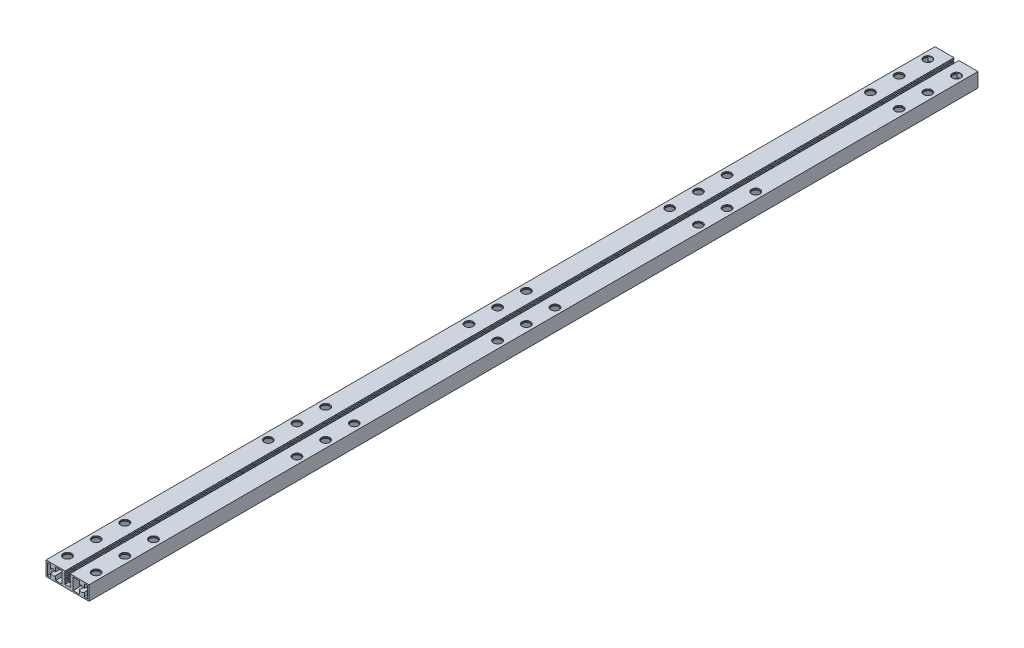
SolidWorks part; units mm, degrees
material "Alliage 6061"
ref_plane "Face" through (0, 0, 0) normal (0, 0, 1) x (1, 0, 0)
ref_plane "Dessus" through (0, 0, 0) normal (0, 1, 0) x (1, 0, 0)
ref_plane "Droite" through (0, 0, 0) normal (1, 0, 0) x (0, 0, -1)
sketch "Esquisse1" plane through (0, 0, 0) normal (0, 0, 1) x (1, 0, 0)
  line L0 (0, 4) -> (0, -4) construction
  line L1 (-12, 4) -> (-1.35, 4)
  line L2 (-12, 4) -> (-12, -4)
  line L3 (-12, -4) -> (12, -4)
  line L4 (12, 4) -> (12, -4)
  line L5 (-12, 0) -> (12, 0) construction
  line L6 (-1.35, 4) -> (-1.35, -2.5)
  line L7 (-1.35, -2.5) -> (1.35, -2.5)
  line L8 (1.35, -2.5) -> (1.35, 4)
  line L9 (1.35, 4) -> (12, 4)
  dimension "D1" = 24
  dimension "D2" = 8
  dimension "D3" = 2.7
  dimension "D4" = 1.5
extrude "Boss.-Extru.1" add sketch "Esquisse1" along normal mid plane 496
sketch "Esquisse2" plane through (0, 0, 248) normal (0, 0, 1) x (1, 0, 0)
  line L0 (-1.35, -2.0613) -> (-2.35, -2.0613) construction
  line L1 (-1.35, -2.5) -> (-1.35, 4) construction
  line L2 (-1.35, -1.7726) -> (-1.35, -2.35)
  line L3 (-1.35, -2.35) -> (-1.85, -2.0613)
  line L4 (-1.85, -2.0613) -> (-1.35, -1.7726)
  dimension "D1" = 0.5
  dimension "D2" = 60
  dimension "D3" = 0.15
extrude "Enlèv. mat.-Extru.1" cut sketch "Esquisse2" against normal through all
pattern_linear "Répétition linéaire1" count 8 spacing 0.8 along (0, 1, 0) of "Enlèv. mat.-Extru.1"
mirror "Symétrie1" about plane through (0, 0, 0) normal (1, 0, 0) of "Répétition linéaire1", "Enlèv. mat.-Extru.1"
sketch "Esquisse3" plane through (0, 0, 248) normal (0, 0, 1) x (1, 0, 0)
  line L0 (0, -4) -> (0, 4.7042) construction
  line L1 (-12, -4) -> (12, -4) construction
  line L5 (-3.1, 3.25) -> (-3.1, -3.25)
  line L6 (-1.35, -2.5) -> (-1.35, -2.35) construction
  line L7 (3.1, 3.25) -> (11.25, 3.25)
  line L8 (-11.25, -3.25) -> (12, -3.25)
  line L11 (-11.25, 3.25) -> (-11.25, -3.25)
  line L12 (-1.35, 3.25) -> (-11.25, 3.25)
  line L13 (-11.25, -3.25) -> (-3.1, -3.25)
  line L14 (-11.25, 3.25) -> (-11.25, -3.25)
  line L15 (-3.1, 3.25) -> (-11.25, 3.25)
  line L16 (11.25, 3.25) -> (11.25, -3.25)
  line L17 (11.25, -3.25) -> (3.1, -3.25)
  line L18 (3.1, 3.25) -> (3.1, -3.25)
  dimension "D1" = 0.75
  dimension "D2" = 1.75
extrude "Enlèv. mat.-Extru.2" cut sketch "Esquisse3" against normal through all
hole_wizard "Dégagement M41" positions "Esquisse5" profile "Esquisse4" hole size "M4" standard "Iso" end condition through all
sketch "Esquisse5" plane through (0, 4, 0) normal (0, 1, 0) x (1, 0, 0)
  line L0 (0, -485.7388) -> (0, -248) construction
  line L1 (-12, -248) -> (12, -248) construction
  line L2 (-1.35, -248) -> (-12, -248) construction
  point P0 (-8, -240)
  point P2 (8, -240)
  dimension "D1" = 8
  dimension "D2" = 16
sketch "Esquisse4" plane through (-8, 4, 240) normal (1, 0, 0) x (0, 0, 1)
  line L0 (0, 0) -> (0, 8)
  line L1 (0, 8) -> (2.35, 8)
  line L2 (2.1, 7.75) -> (2.1, 0.25)
  line L3 (2.1, 0.25) -> (2.35, 0)
  line L5 (2.35, 0) -> (0, 0)
  line L6 (-2.1, 0.25) -> (-2.35, 0) construction
  line L7 (2.35, 8) -> (2.1, 7.75)
  line L8 (-2.35, 8) -> (-2.1, 7.75) construction
  line L11 (0, -6.35) -> (0, 107.95) construction
  dimension "Diamètre du perçage jusqu'au prochain" = 4.2
  dimension "Profondeur du perçage jusqu'au prochain" = 8
  dimension "Diamètre du fraisage entrant" = 4.7
  dimension "Angle du fraisage entrant" = 90
  dimension "Diamètre du fraisage débouchant" = 4.7
  dimension "Angle du fraisage débouchant" = 90
pattern_linear "Répétition linéaire2" count 31 spacing 16 along (0, 0, -1) skipping (3, 0), (4, 0), (5, 0), (6, 0), (10, 0), (11, 0), (12, 0), (13, 0), (17, 0), (18, 0), (19, 0), (20, 0), (24, 0), (25, 0), (26, 0), (27, 0) of "Dégagement M41"
pattern_linear "Répétition linéaire3" [suppressed] count 9 spacing 16
sketch "Esquisse6" plane through (0, 0, 248) normal (0, 0, 1) x (1, 0, 0)
  line L0 (-3.1, 3.25) -> (-11.25, 3.25) construction
  line L1 (-9.375, 3.25) -> (-6.625, 3.25)
  line L2 (-9.375, 3.25) -> (-9.375, -3.25)
  line L3 (-8, 3.25) -> (-8, -3.25) construction
  line L4 (-6.625, 3.25) -> (-6.625, -3.25)
  line L5 (-11.25, -3.25) -> (-3.1, -3.25) construction
  line L6 (-9.375, -3.25) -> (-6.625, -3.25)
  line L7 (0, 0) -> (0, 5.6821) construction
  dimension "D1" = 8
  dimension "D2" = 2.75
extrude "Boss.-Extru.2" add sketch "Esquisse6" against normal up to surface (6.4127 mm away)
sketch "Esquisse9" plane through (0, 0, 248) normal (0, 0, 1) x (1, 0, 0)
  line L0 (0, 0) -> (0, 5.6821) construction
  line L1 (6.625, -3.25) -> (6.625, 3.25)
  line L2 (9.375, -3.25) -> (6.625, -3.25)
  line L3 (9.375, 3.25) -> (9.375, -3.25)
  line L4 (-6.625, 3.25) -> (-9.375, 3.25)
  line L5 (-6.625, -3.25) -> (-6.625, 3.25)
  line L6 (-9.375, -3.25) -> (-6.625, -3.25)
  line L7 (-9.375, 3.25) -> (-9.375, -3.25)
  line L8 (-6.625, 3.25) -> (-9.375, 3.25) construction
  line L9 (-6.625, -3.25) -> (-6.625, 3.25) construction
  line L10 (-9.375, -3.25) -> (-6.625, -3.25) construction
  line L11 (-9.375, 3.25) -> (-9.375, -3.25) construction
  line L12 (6.625, 3.25) -> (9.375, 3.25)
  dimension "D1" = 0
extrude "Boss.-Extru.3" add sketch "Esquisse9" against normal up to surface (6.4127 mm away)
hole_wizard "Trou taraudé M41" positions "Esquisse8" profile "Esquisse7" tap size "M4" standard "Iso" end condition up to next
sketch "Esquisse8" plane through (0, 0, 248) normal (0, 0, 1) x (1, 0, 0)
  line L0 (-8, 4) -> (-8, -4) construction
  line L1 (-1.35, 4) -> (-12, 4) construction
  line L2 (-12, -4) -> (12, -4) construction
  line L3 (-9.375, 3.25) -> (-9.375, -3.25) construction
  line L4 (-6.625, -3.25) -> (-6.625, 3.25) construction
  line L5 (8, 4) -> (8, -4) construction
  line L6 (12, 4) -> (1.35, 4) construction
  line L7 (6.625, 3.25) -> (6.625, -3.25) construction
  line L8 (9.375, -3.25) -> (9.375, 3.25) construction
  point P0 (-8, 0)
  point P23 (8, 0)
sketch "Esquisse7" plane through (-8, 0, 248) normal (1, 0, 0) x (0, -1, 0)
  line L0 (0, 0) -> (0, 5.9)
  line L1 (0, 5.9) -> (1.65, 5.9)
  line L2 (1.65, 5.9) -> (1.65, 0)
  line L5 (1.65, 0) -> (0, 0)
  line L11 (0, -6.35) -> (0, 107.95) construction
  dimension "Diamètre du trou pour taraudage jusqu'au prochain" = 3.3
  dimension "Profondeur du trou pour taraudage jusqu'au prochain" = 5.9
cosmetic thread "Filetage de perçage2" parameters "D1"=6.8392, "D2"=4
cosmetic thread "Filetage de perçage3" parameters "D1"=6.8392, "D2"=4
sketch "Esquisse10" plane through (0, 0, -248) normal (0, 0, -1) x (-1, 0, 0)
  line L0 (-11.25, 3.25) -> (-3.1, 3.25) construction
  line L1 (-9.375, 3.25) -> (-6.625, 3.25)
  line L2 (-9.375, 3.25) -> (-9.375, -3.25)
  line L3 (-9.375, -3.25) -> (-6.625, -3.25)
  line L4 (-6.625, 3.25) -> (-6.625, -3.25)
  line L5 (-3.1, -3.25) -> (-11.25, -3.25) construction
  line L6 (-9.375, 3.25) -> (-9.375, 0.9121) construction
  line L7 (-6.625, 0.9121) -> (-6.625, 3.25) construction
extrude "Boss.-Extru.4" add sketch "Esquisse10" against normal up to surface (6.4127 mm away)
sketch "Esquisse11" plane through (0, 0, -248) normal (0, 0, -1) x (-1, 0, 0)
  line L0 (3.1, 3.25) -> (11.25, 3.25) construction
  line L1 (6.625, 3.25) -> (9.375, 3.25)
  line L2 (6.625, 3.25) -> (6.625, -3.25)
  line L3 (6.625, -3.25) -> (9.375, -3.25)
  line L4 (9.375, 3.25) -> (9.375, -3.25)
  line L5 (11.25, -3.25) -> (3.1, -3.25) construction
  line L6 (6.625, 3.25) -> (6.625, 0.9121) construction
  line L7 (9.375, 0.9121) -> (9.375, 3.25) construction
extrude "Boss.-Extru.5" add sketch "Esquisse11" against normal up to surface (6.4127 mm away)
hole_wizard "Trou taraudé M42" positions "Esquisse13" profile "Esquisse12" tap size "M4" standard "Iso" end condition up to next
sketch "Esquisse13" plane through (0, 0, -248) normal (0, 0, -1) x (-1, 0, 0)
  line L0 (-8, 4) -> (-8, -4) construction
  line L1 (-12, 4) -> (-1.35, 4) construction
  line L2 (12, -4) -> (-12, -4) construction
  line L3 (8, 4) -> (8, -4) construction
  line L4 (1.35, 4) -> (12, 4) construction
  line L5 (6.625, 3.25) -> (6.625, -3.25) construction
  line L6 (9.375, -3.25) -> (9.375, 3.25) construction
  line L7 (-9.375, 3.25) -> (-9.375, -3.25) construction
  line L8 (-6.625, -3.25) -> (-6.625, 3.25) construction
  point P0 (-8, 0)
  point P2 (8, 0)
sketch "Esquisse12" plane through (8, 0, -248) normal (1, 0, 0) x (0, 1, 0)
  line L0 (0, 0) -> (0, 5.9)
  line L1 (0, 5.9) -> (1.65, 5.9)
  line L2 (1.65, 5.9) -> (1.65, 0)
  line L5 (1.65, 0) -> (0, 0)
  line L11 (0, -6.35) -> (0, 107.95) construction
  dimension "Diamètre du trou pour taraudage jusqu'au prochain" = 3.3
  dimension "Profondeur du trou pour taraudage jusqu'au prochain" = 5.9
cosmetic thread "Filetage de perçage4" [suppressed] parameters "D1"=0, "D2"=4.3
cosmetic thread "Filetage de perçage5" [suppressed] parameters "D1"=0, "D2"=4.3
